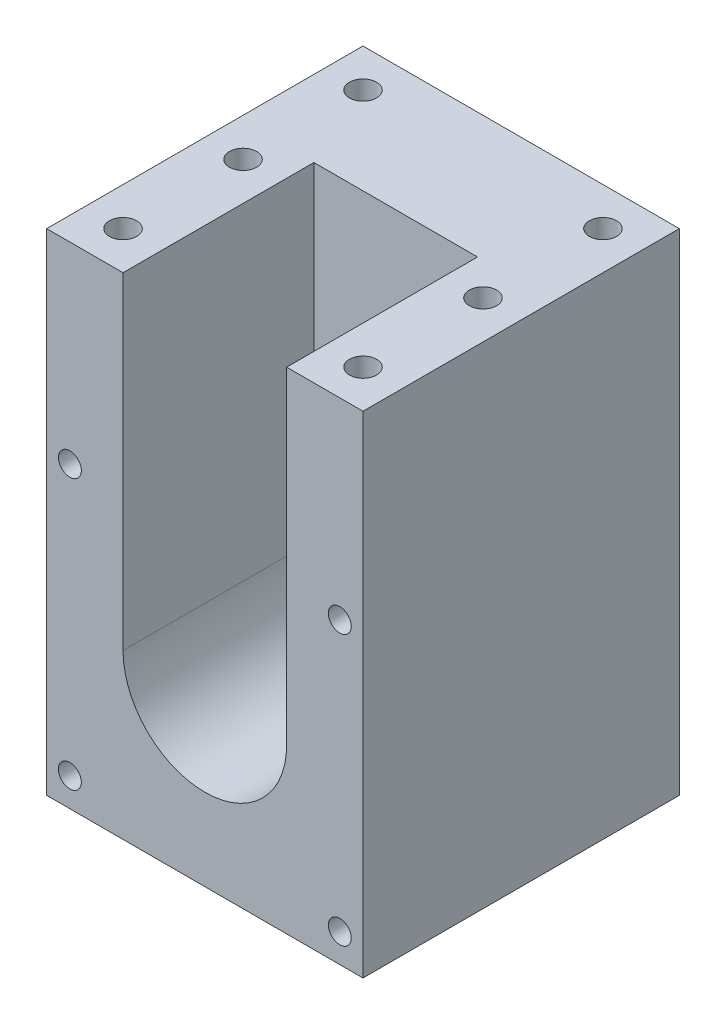
SolidWorks part; units mm, degrees
ref_plane "Front Plane" through (0, 0, 0) normal (0, 0, 1) x (1, 0, 0)
ref_plane "Top Plane" through (0, 0, 0) normal (0, 1, 0) x (1, 0, 0)
ref_plane "Right Plane" through (0, 0, 0) normal (1, 0, 0) x (0, 0, -1)
sketch "Sketch2" plane through (0, 0, 0) normal (0, 1, 0) x (1, 0, 0)
  line L0 (-29, 0) -> (0, 0)
  line L1 (29, 0) -> (29, 58)
  line L2 (29, 58) -> (-29, 58)
  line L3 (-29, 58) -> (-29, 0)
  line L4 (0, 0) -> (29, 0)
  dimension "D1" = 58
  dimension "D2" = 58
extrude "Boss-Extrude1" add sketch "Sketch2" along normal blind 90
sketch "Sketch3" plane through (0, 0, -58) normal (0, 0, 1) x (1, 0, 0)
  line L0 (0, 30) -> (0, 0) construction
  line L2 (-30, 30) -> (30, 30) construction
  line L5 (0, 30) -> (0, 60) construction
  circle A0 centre (0, 30) radius 11
  dimension "D1" = 22
  dimension "D2" = 60
extrude "Cut-Extrude1" cut sketch "Sketch3" along normal blind 13
sketch "Sketch4" plane through (0, 0, -45) normal (0, 0, -1) x (-1, 0, 0)
  circle A0 centre (0, 30) radius 8
  dimension "D1" = 16
extrude "Cut-Extrude2" cut sketch "Sketch4" against normal through all
sketch "Sketch5" plane through (0, 0, 0) normal (0, 0, 1) x (1, 0, 0)
  line L0 (-30, 30) -> (30, 30) construction
  circle A0 centre (0, 30) radius 15
  dimension "D1" = 30
extrude "Cut-Extrude3" cut sketch "Sketch5" against normal offset from surface (35 mm away) 10 up to face at (-8, 30, -45)
sketch "Sketch6" plane through (0, 0, 0) normal (0, 0, 1) x (1, 0, 0)
  line L1 (-15, 30) -> (-15, 90)
  line L2 (-30, 30) -> (30, 30) construction
  line L3 (-29, 90) -> (29, 90) construction
  line L4 (-15, 90) -> (15, 90)
  line L5 (15, 90) -> (15, 30)
  line L6 (-15, 30) -> (15, 30)
  circle A0 centre (0, 30) radius 15 construction
extrude "Cut-Extrude4" cut sketch "Sketch6" against normal up to surface (35 mm away) up to face at (15, 30, -35)
hole_wizard "M6 Tapped Hole" positions "Sketch9" profile "Sketch10" tap size "M6" standard "ISO" end condition through all
sketch "Sketch9" plane through (559.8458, 100, -1460.8861) normal (0, 1, 0) x (-1, 0, 0)
  point P0 (514.8458, 897.4716)
  point P3 (537.8458, 897.4716)
  point P6 (581.8458, 897.4716)
  point P9 (604.8458, 897.4716)
  point P12 (514.8458, 1450.8861)
  point P15 (514.8458, 1412.8861)
  point P18 (537.8458, 1453.8861)
  point P21 (537.8458, 1409.8861)
  point P24 (581.8458, 1453.8861)
  point P27 (581.8458, 1409.8861)
  point P30 (604.8458, 1450.8861)
  point P33 (604.8458, 1412.8861)
  point P36 (514.8458, 1431.8861)
  point P39 (537.8458, 1431.8861)
  point P43 (581.8458, 1431.8861)
  point P46 (604.8458, 1431.8861)
sketch "Sketch10" plane through (45, 100, -563.4145) normal (1, 0, 0) x (0, 0, 1)
  line L0 (0, 0) -> (0, 100)
  line L1 (0, 100) -> (2.5, 100)
  line L2 (2.5, 100) -> (2.5, 0)
  line L3 (2.5, 0) -> (0, 0)
  line L4 (0, -6.35) -> (0, 107.95) construction
  dimension "Thread Major Dia." = 5
  dimension "Thru Tap Drill Depth" = 100
hole_wizard "M5 Tapped Hole1" positions "Sketch11" profile "Sketch12" tap size "M5" standard "ISO" end condition through all
sketch "Sketch11" plane through (559.8458, -258.9049, 0) normal (0, 0, 1) x (-1, 0, 0)
  point P0 (535.0971, -264.1562)
  point P3 (584.5945, -264.1562)
  point P6 (535.0971, -313.6537)
  point P9 (584.5945, -313.6537)
sketch "Sketch12" plane through (24.7487, 5.2513, 0) normal (1, 0, 0) x (0, -1, 0)
  line L0 (0, 0) -> (0, 58)
  line L1 (0, 58) -> (2.1, 58)
  line L2 (2.1, 58) -> (2.1, 0)
  line L3 (2.1, 0) -> (0, 0)
  line L4 (0, -6.35) -> (0, 107.95) construction
  dimension "Thread Major Dia." = 4.2
  dimension "Thru Tap Drill Depth" = 58
